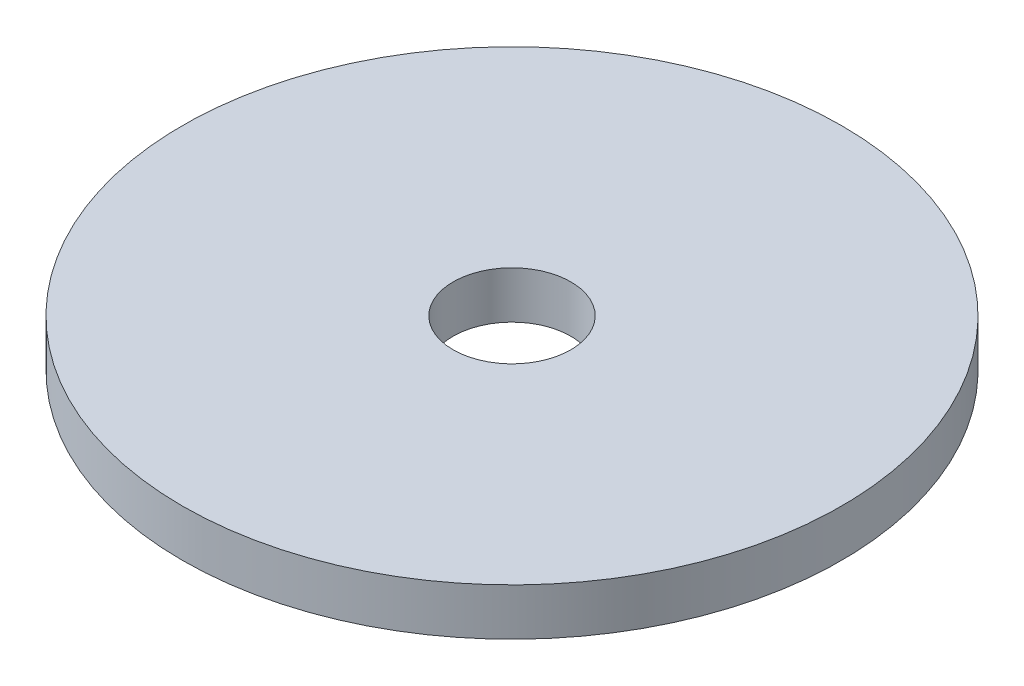
SolidWorks part; units mm, degrees
ref_plane "Front Plane" through (0, 0, 0) normal (0, 0, 1) x (1, 0, 0)
ref_plane "Top Plane" through (0, 0, 0) normal (0, 1, 0) x (1, 0, 0)
ref_plane "Right Plane" through (0, 0, 0) normal (1, 0, 0) x (0, 0, -1)
sketch "Sketch1" plane through (0, 0, 0) normal (0, 1, 0) x (1, 0, 0)
  circle A0 centre (0, 0) radius 14
  dimension "D1" = 28
extrude "Boss-Extrude1" add sketch "Sketch1" along normal blind 2
sketch "Sketch2" plane through (0, 0, 0) normal (0, 1, 0) x (1, 0, 0)
  circle A0 centre (0, 0) radius 2.5
  dimension "D1" = 5
extrude "Cut-Extrude2" cut sketch "Sketch2" along normal blind 6
